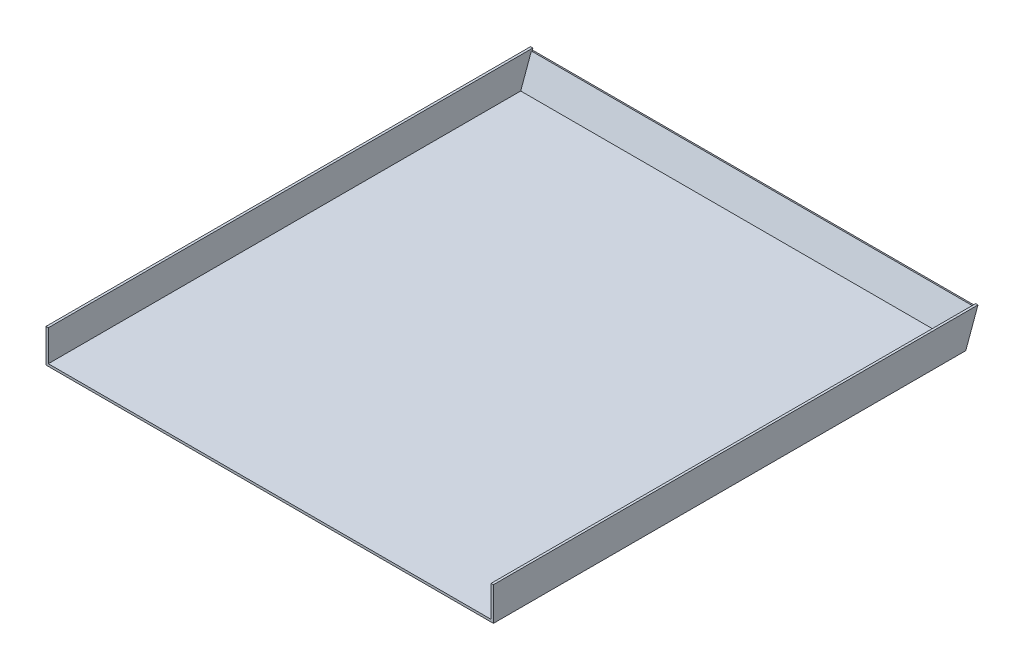
SolidWorks part; units mm, degrees
ref_plane "Front Plane" through (0, 0, 0) normal (0, 0, 1) x (1, 0, 0)
ref_plane "Top Plane" through (0, 0, 0) normal (0, 1, 0) x (1, 0, 0)
ref_plane "Right Plane" through (0, 0, 0) normal (1, 0, 0) x (0, 0, -1)
sketch "Sketch1" plane through (0, 0, 0) normal (0, 1, 0) x (1, 0, 0)
  line L1 (-143.5, -151.5) -> (143.5, -151.5)
  line L2 (-143.5, -151.5) -> (-143.5, 151.5)
  line L3 (-143.5, 151.5) -> (143.5, 151.5)
  line L4 (143.5, -151.5) -> (143.5, 151.5)
  line L5 (-143.5, -151.5) -> (143.5, 151.5) construction
  line L6 (-143.5, 151.5) -> (143.5, -151.5) construction
  point P0 (0, 0)
  dimension "D1" = 287
  dimension "D2" = 303
extrude "Boss-Extrude1" add sketch "Sketch1" along normal blind 1.5 contours L2 L3 L4 L1
sketch "Sketch8" plane through (0, 1.5, 0) normal (0, 1, 0) x (1, 0, 0)
  line L0 (-143.5, -151.5) -> (143.5, -151.5) construction
  line L1 (-143.5, 151.5) -> (-142, 151.5)
  line L2 (-143.5, 151.5) -> (-143.5, -151.5)
  line L3 (-143.5, -151.5) -> (-142, -151.5)
  line L4 (-142, 151.5) -> (-142, -151.5)
  line L6 (143.5, 151.5) -> (142, 151.5)
  line L7 (143.5, 151.5) -> (143.5, -151.5)
  line L8 (143.5, -151.5) -> (142, -151.5)
  line L9 (142, 151.5) -> (142, -151.5)
  dimension "D1" = 1.5
  dimension "D2" = 1.5
extrude "Boss-Extrude8" add sketch "Sketch8" along normal blind 20
sketch "Sketch9" plane through (-143.5, 0, 0) normal (-1, 0, 0) x (0, 0, 1)
  line L0 (-151.5, 21.5) -> (-151.5, 0) construction
  line L1 (151.5, 0) -> (-151.5, 0)
  line L2 (151.5, 0) -> (151.5, 1.5)
  line L3 (151.5, 1.5) -> (-151.5, 1.5)
  line L4 (-151.5, 0) -> (-151.5, 1.5)
  dimension "D1" = 1.5
extrude "Boss-Extrude9" [suppressed] add sketch "Sketch9" along normal blind 20
sketch "Sketch10" plane through (143.5, 0, 0) normal (1, 0, 0) x (0, 0, -1)
  line L0 (-151.5, 21.5) -> (-151.5, 0) construction
  line L1 (151.5, 0) -> (-151.5, 0)
  line L2 (151.5, 0) -> (151.5, 1.5)
  line L3 (151.5, 1.5) -> (-151.5, 1.5)
  line L4 (-151.5, 0) -> (-151.5, 1.5)
  dimension "D1" = 1.5
extrude "Boss-Extrude10" [suppressed] add sketch "Sketch10" along normal blind 20
sketch "Sketch11" [suppressed] plane through (0, 0, -151.5) normal (0, 0, -1) x (-1, 0, 0)
  line L0 (163.5, 0) -> (-163.5, 0) construction
  line L1 (143.5, 1.5) -> (-143.5, 1.5)
  line L2 (143.5, 1.5) -> (143.5, 0)
  line L3 (143.5, 0) -> (-143.5, 0)
  line L4 (-143.5, 1.5) -> (-143.5, 0)
extrude "Boss-Extrude11" [suppressed] add sketch "Sketch11" along normal blind 20
sketch "Sketch12" plane through (-143.5, 0, 0) normal (-1, 0, 0) x (0, 0, 1)
  line L0 (-151.5, 21.5) -> (-159.3254, 21.5)
  line L1 (-159.3254, 21.5) -> (-151.5, 0)
  line L2 (-151.5, 21.5) -> (-151.5, 0) construction
  line L3 (-151.5, 0) -> (-151.5, 21.5)
  dimension "D1" = 20
extrude "Boss-Extrude12" add sketch "Sketch12" against normal up to surface (1.5 mm away) up to face at (-142, 11.5, 0)
sketch "Sketch13" plane through (143.5, 0, 0) normal (1, 0, 0) x (0, 0, -1)
  line L0 (151.5, 0) -> (151.5, 21.5)
  line L1 (151.5, 21.5) -> (159.3254, 21.5)
  line L2 (159.3254, 21.5) -> (151.5, 0)
  dimension "D1" = 20
extrude "Boss-Extrude13" add sketch "Sketch13" against normal up to surface (1.5 mm away) up to face at (142, 11.5, 0)
sketch "Sketch15" plane through (0, 0, 0) normal (1, 0, 0) x (0, 0, -1)
  line L0 (151.5, 1.5) -> (158.3404, 20.2939)
  line L1 (-151.5, 0) -> (151.5, 0) construction
  line L2 (151.5, 1.5) -> (151.5, 0) construction
  line L3 (158.3404, 20.2939) -> (159.7499, 19.7808)
  line L4 (159.7499, 19.7808) -> (152.9095, 0.987)
  line L6 (151.5, 1.5) -> (151.5, 0)
  line L7 (151.5, 1.5) -> (-151.5, 1.5) construction
  arc A0 (152.9095, 0.987) -> (151.5, 0) centre (151.5, 1.5) cw
  dimension "D1" = 110
  dimension "D2" = 0
  dimension "D3" = 20
  dimension "D4" = 1.5
  dimension "D5" = 0
extrude "Boss-Extrude14" add sketch "Sketch15" along normal up to surface and the other way up to surface up to face at (142, 9.2, -31.8651) other way up to face at (-142, 9.2, -31.8651)
